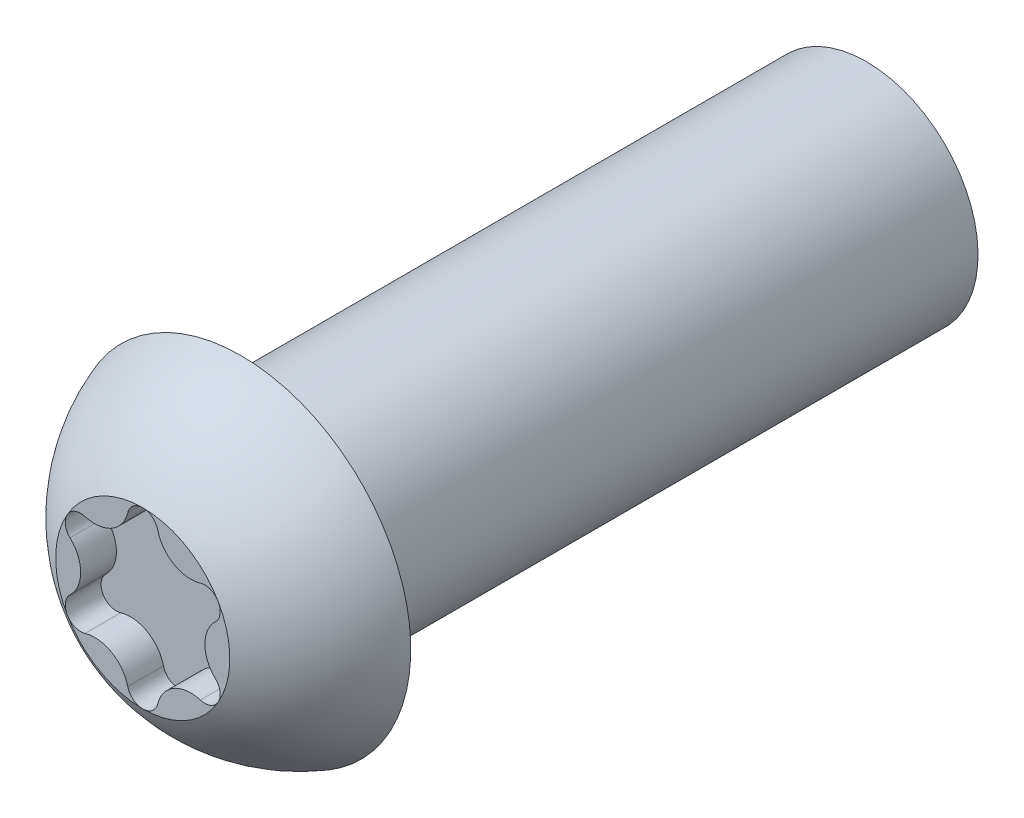
SolidWorks part; units mm, degrees
material "AISI Acier à outil type A2"
ref_plane "Face" through (0, 0, 0) normal (0, 0, 1) x (1, 0, 0)
ref_plane "Dessus" through (0, 0, 0) normal (0, 1, 0) x (1, 0, 0)
ref_plane "Droite" through (0, 0, 0) normal (1, 0, 0) x (0, 0, -1)
sketch "Esquisse1" plane through (0, 0, 0) normal (1, 0, 0) x (0, 0, -1)
  line L0 (-2.2, 0) -> (-2.2, 1.95)
  line L1 (0, 3.8) -> (0, 2.5)
  line L2 (0, 2.5) -> (14, 2.5)
  line L3 (14, 2.5) -> (14, 0)
  line L4 (14, 0) -> (-2.2, 0)
  line L5 (-2.2, 0) -> (-18.0711, 0) construction
  arc A0 (-2.2, 1.95) -> (0, 3.8) centre (1.3176, 0) cw
  dimension "M" = 5
  dimension "DH" = 7.6
  dimension "A" = 3.9
  dimension "K" = 2.2
  dimension "L" = 14
revolve "Révolution1" add sketch "Esquisse1" angle 360 about L5
cosmetic thread "Représentation de filetage1" [suppressed] parameters "D2"=1.548
cosmetic thread "Représentation de filetage2" [suppressed] parameters "D2"=1.993
cosmetic thread "Représentation de filetage3" [suppressed] parameters "D2"=2.439
cosmetic thread "Représentation de filetage4" parameters "D2"=3.22
cosmetic thread "Représentation de filetage5" [suppressed] parameters "D2"=4.11
cosmetic thread "Représentation de filetage6" [suppressed] parameters "D2"=4.891
cosmetic thread "Représentation de filetage7" [suppressed] parameters "D2"=6.891
sketch "Esquisse2" plane through (0, 0, 2.2) normal (0, 0, 1) x (1, 0, 0)
  line L0 (0, 1.8503) -> (0, -1.9994) construction
  line L1 (-2.0152, 0) -> (2.4489, 0) construction
  line L2 (0, 0) -> (-0.3794, 1.9074) construction
  line L3 (0, 0) -> (0.3821, 1.9207) construction
  line L4 (0, 0) -> (1.3768, 1.2074) construction
  line L5 (0, 0) -> (1.8862, 1.089) construction
  line L6 (0, 1.6052) -> (-1.3901, 0.8026) construction
  line L7 (-1.3901, 0.8026) -> (-1.3901, -0.8026) construction
  line L8 (-1.3901, -0.8026) -> (0, -1.6052) construction
  line L9 (0, -1.6052) -> (1.3901, -0.8026) construction
  line L10 (1.3901, -0.8026) -> (1.3901, 0.8026) construction
  line L11 (1.3901, 0.8026) -> (0, 1.6052) construction
  circle A0 centre (0, 0) radius 1.95 construction
  circle A1 centre (0, 0) radius 1.95 construction
  arc A2 (-0.3353, 1.6857) -> (0.3353, 1.6857) centre (0, 1.6052) cw
  arc A3 (0.3353, 1.6857) -> (1.2922, 1.1332) centre (1.0759, 1.8634) ccw
  circle A4 centre (0, 0) radius 1.3901 construction
  arc A5 (1.2922, 1.1332) -> (1.6275, 0.5525) centre (1.3901, 0.8026) cw
  arc A6 (1.6275, 0.5525) -> (1.6275, -0.5525) centre (2.1517, 0) ccw
  arc A7 (1.6275, -0.5525) -> (1.2922, -1.1332) centre (1.3901, -0.8026) cw
  arc A8 (1.2922, -1.1332) -> (0.3353, -1.6857) centre (1.0759, -1.8634) ccw
  arc A9 (0.3353, -1.6857) -> (-0.3353, -1.6857) centre (0, -1.6052) cw
  arc A10 (-0.3353, -1.6857) -> (-1.2922, -1.1332) centre (-1.0759, -1.8634) ccw
  arc A11 (-1.2922, -1.1332) -> (-1.6275, -0.5525) centre (-1.3901, -0.8026) cw
  arc A12 (-1.6275, -0.5525) -> (-1.6275, 0.5525) centre (-2.1517, 0) ccw
  arc A13 (-1.6275, 0.5525) -> (-1.2922, 1.1332) centre (-1.3901, 0.8026) cw
  arc A14 (-1.2922, 1.1332) -> (-0.3353, 1.6857) centre (-1.0759, 1.8634) ccw
  point P0 (0.6951, 1.2039)
  point P14 (0, 1.95)
  dimension "D1" = 22.5
  dimension "D2" = 11.25
  dimension "D3" = 6
extrude "Enlèv. mat.-Extru.1" cut sketch "Esquisse2" against normal blind 0.8
equation "\"D2@Esquisse2\" = \"D1@Esquisse2\"/2"
